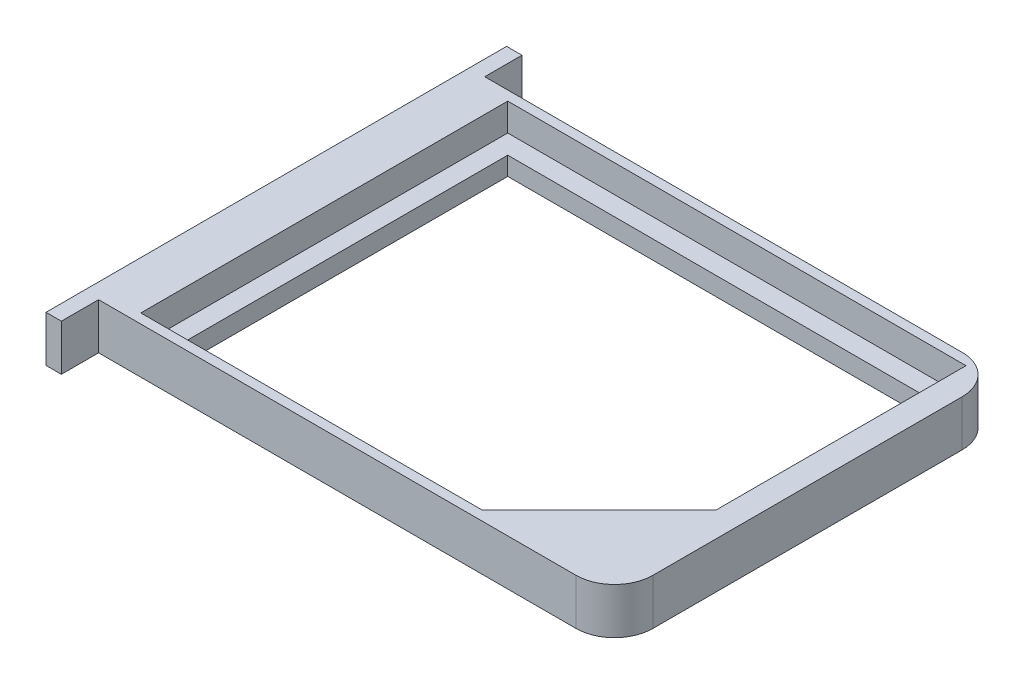
SolidWorks part; units mm, degrees
ref_plane "Front Plane" through (0, 0, 0) normal (0, 0, 1) x (1, 0, 0)
ref_plane "Top Plane" through (0, 0, 0) normal (0, 1, 0) x (1, 0, 0)
ref_plane "Right Plane" through (0, 0, 0) normal (1, 0, 0) x (0, 0, -1)
sketch "Sketch1" plane through (0, 0, 0) normal (0, 1, 0) x (1, 0, 0)
  line L1 (0, 0) -> (15.7988, 0)
  line L2 (0, 0) -> (0, 12.7762)
  line L3 (0, 12.7762) -> (15.7988, 12.7762)
  line L4 (17.0688, 1.27) -> (17.0688, 11.5062)
  arc A0 (15.7988, 12.7762) -> (17.0688, 11.5062) centre (15.7988, 11.5062) cw
  arc A1 (15.7988, 0) -> (17.0688, 1.27) centre (15.7988, 1.27) ccw
  point P7 (17.0688, 12.7762)
  point P10 (17.0688, 0)
  dimension "D3" = 1.27
  dimension "D1" = 17.0688
  dimension "D2" = 12.7762
extrude "Boss-Extrude1" add sketch "Sketch1" along normal blind 1.524
sketch "Sketch2" plane through (0, 1.524, 0) normal (0, 1, 0) x (1, 0, 0)
  line L0 (0, 6.3881) -> (17.0688, 6.3881) construction
  line L1 (1.0795, 12.4587) -> (16.2433, 12.4587)
  line L2 (1.0795, 12.4587) -> (1.0795, 0.3175)
  line L3 (1.0795, 0.3175) -> (16.2433, 0.3175)
  line L4 (16.2433, 12.4587) -> (16.2433, 0.3175)
  line L5 (0, 12.7762) -> (0, 0) construction
  line L6 (17.0688, 1.27) -> (17.0688, 11.5062) construction
  line L7 (7.8994, 12.7762) -> (7.8994, 0) construction
  line L8 (15.7988, 12.7762) -> (0, 12.7762) construction
  line L9 (0, 0) -> (15.7988, 0) construction
  line L10 (8.6614, 12.4587) -> (8.6614, 0.3175) construction
  line L11 (1.0795, 6.3881) -> (16.2433, 6.3881) construction
  dimension "D1" = 15.1638
  dimension "D2" = 12.1412
  dimension "D3" = 0.762
extrude "Cut-Extrude1" cut sketch "Sketch2" against normal through all
sketch "Sketch3" plane through (0, 0, 0) normal (0, 1, 0) x (1, 0, 0)
  line L0 (12.3694, 0.3175) -> (16.2433, 4.1914)
  line L1 (1.0795, 0.3175) -> (16.2433, 0.3175) construction
  line L2 (16.2433, 0.3175) -> (16.2433, 12.4587) construction
  line L3 (16.2433, 4.1914) -> (16.2433, 0.3175)
  line L4 (16.2433, 0.3175) -> (12.3694, 0.3175)
  dimension "D1" = 45
extrude "Boss-Extrude2" add sketch "Sketch3" along normal blind 1.524
sketch "Sketch5" plane through (0, 0, 0) normal (0, 1, 0) x (1, 0, 0)
  line L16 (1.7145, 11.8237) -> (1.7145, 0.9525)
  line L17 (1.7145, 0.9525) -> (12.1064, 0.9525)
  line L18 (12.1064, 0.9525) -> (15.6083, 4.4544)
  line L19 (15.6083, 4.4544) -> (15.6083, 11.8237)
  line L20 (15.6083, 11.8237) -> (1.7145, 11.8237)
  line L21 (1.0795, 0.3175) -> (12.3694, 0.3175)
  line L22 (12.3694, 0.3175) -> (16.2433, 4.1914)
  line L23 (16.2433, 4.1914) -> (16.2433, 12.4587)
  line L24 (16.2433, 12.4587) -> (1.0795, 12.4587)
  line L25 (1.0795, 12.4587) -> (1.0795, 0.3175)
  line L26 (1.0795, 0.3175) -> (12.3694, 0.3175)
  line L27 (12.3694, 0.3175) -> (16.2433, 4.1914)
  line L28 (16.2433, 4.1914) -> (16.2433, 12.4587)
  line L29 (16.2433, 12.4587) -> (1.0795, 12.4587)
  line L30 (1.0795, 12.4587) -> (1.0795, 0.3175)
  dimension "D1" = 0
  dimension "D2" = 0.635
extrude "Boss-Extrude3" add sketch "Sketch5" along normal blind 0.6096
sketch "Sketch7" plane through (0, 0, 0) normal (-1, 0, 0) x (0, 0, 1)
  line L0 (-6.3881, 1.524) -> (-6.3881, 0) construction
  line L1 (-12.7762, 1.524) -> (0, 1.524) construction
  line L2 (-12.7762, 0) -> (0, 0) construction
  line L3 (-6.3881, 1.524) -> (-6.3881, 0) construction
  line L4 (-14.0081, 1.524) -> (1.2319, 1.524)
  line L5 (-14.0081, 1.524) -> (-14.0081, 0)
  line L6 (-14.0081, 0) -> (1.2319, 0)
  line L7 (1.2319, 1.524) -> (1.2319, 0)
  line L8 (-14.0081, 0.762) -> (1.2319, 0.762) construction
  dimension "D2" = 15.24
extrude "Boss-Extrude4" add sketch "Sketch7" along normal blind 0.508
